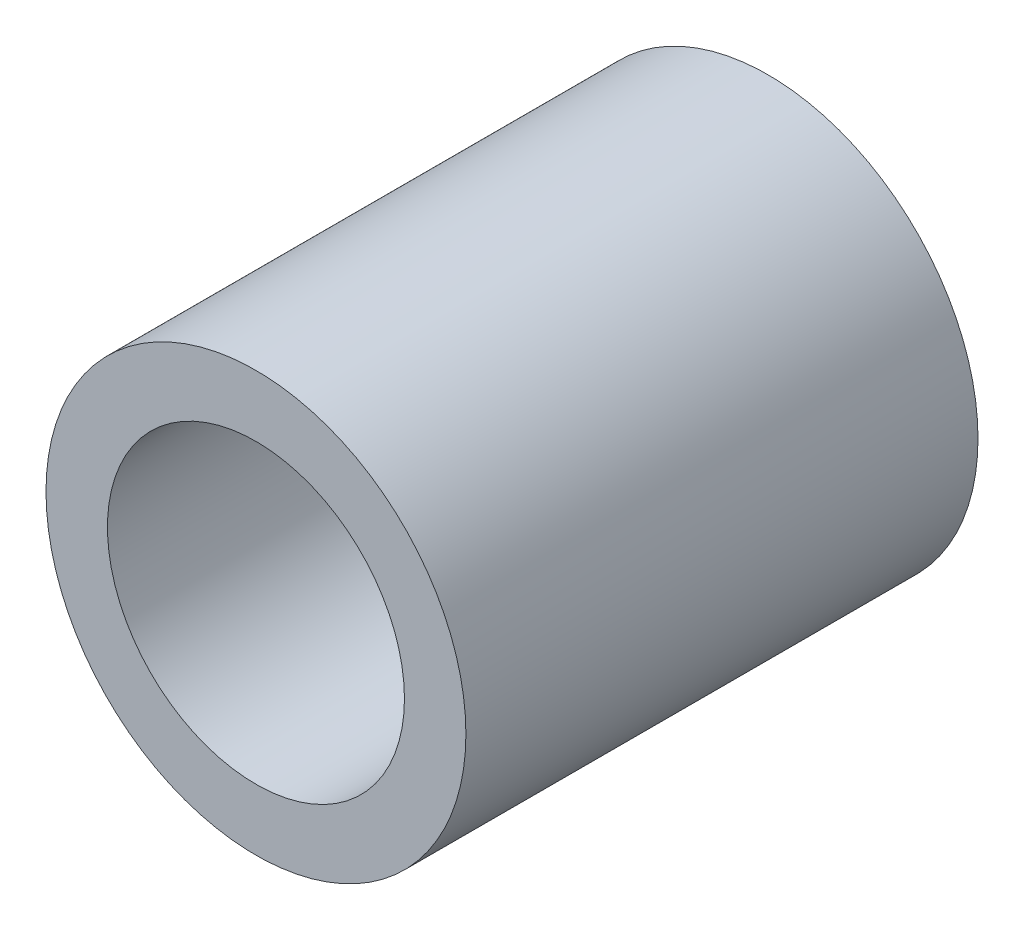
SolidWorks part; units mm, degrees
ref_plane "Front Plane" through (0, 0, 0) normal (0, 0, 1) x (1, 0, 0)
ref_plane "Top Plane" through (0, 0, 0) normal (0, 1, 0) x (1, 0, 0)
ref_plane "Right Plane" through (0, 0, 0) normal (1, 0, 0) x (0, 0, -1)
sketch "Sketch1" plane through (0, 0, 0) normal (0, 0, 1) x (1, 0, 0)
  circle A0 centre (0, 0) radius 1.45
  circle A1 centre (0, 0) radius 2.05
  dimension "D1" = 0.6
  dimension "D2" = 4.1
extrude "Boss-Extrude1" add sketch "Sketch1" along normal blind 5
